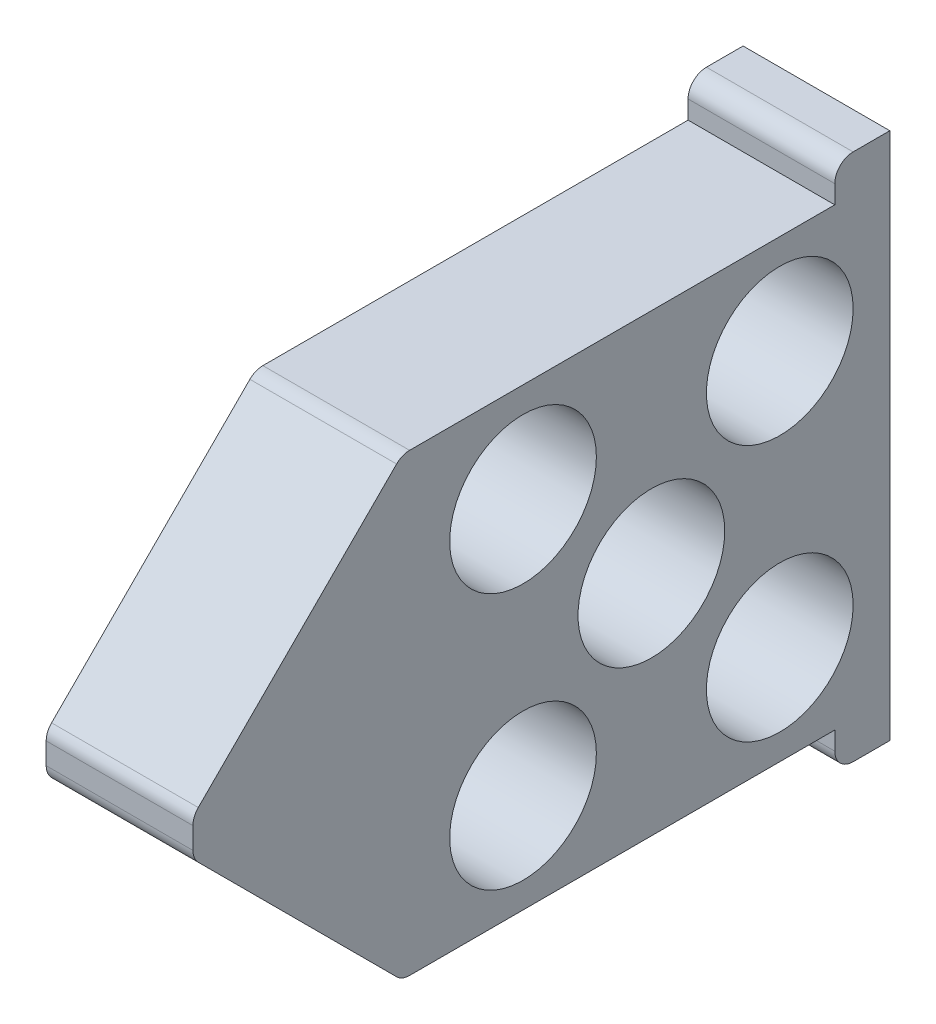
SolidWorks part; units mm, degrees
material "6061-T6 (SS)"
ref_plane "Front Plane" through (0, 0, 0) normal (0, 0, 1) x (1, 0, 0)
ref_plane "Top Plane" through (0, 0, 0) normal (0, 1, 0) x (1, 0, 0)
ref_plane "Right Plane" through (0, 0, 0) normal (1, 0, 0) x (0, 0, -1)
sketch "Sketch1" plane through (0, 0, 0) normal (1, 0, 0) x (0, 0, -1)
  line L0 (-6, 6.2) -> (6, -6.2) construction
  line L2 (-6, 6.2) -> (-6, -6.2) construction
  line L3 (-5.8, 6.2) -> (-11.5, 0.5)
  line L4 (6, 6.2) -> (6, -6.2) construction
  line L5 (6, 6.2) -> (6, 7.2)
  line L6 (6, 7.2) -> (7.5, 7.2)
  line L7 (7.5, 7.2) -> (7.5, -7.2)
  line L8 (-4.2787, 0) -> (7.198, 0) construction
  line L9 (6, -6.2) -> (6, -7.2)
  line L10 (6, -7.2) -> (7.5, -7.2)
  line L11 (6, 6.2) -> (-5.8, 6.2)
  line L12 (-11.5, 6.2) -> (-11.5, -6.2) construction
  line L13 (-11.5, 0.5) -> (-11.5, -0.5)
  line L14 (-5.8, -6.2) -> (-11.5, -0.5)
  line L15 (6, -6.2) -> (-5.8, -6.2)
  point P4 (0, 0)
  point P13 (7.5, 0)
  point P16 (-11.5, 0)
  point P18 (-11.5, 0)
  dimension "D1" = 5.7
  dimension "D2" = 1
  dimension "D3" = 1.5
  dimension "D4" = 1
  dimension "D5" = 17.5
  dimension "D6" = 45
  dimension "D7" = 0.2
extrude "Boss-Extrude1" add sketch "Sketch1" along normal blind 4
fillet "Fillet1" [suppressed] radius 2
fillet "Fillet2" radius 0.5 6 edges at (2, -7.2, -6) (2, 7.2, -6) (2, -6.2, 5.8) (2, -0.5, 11.5) (2, 0.5, 11.5) (2, 6.2, 5.8)
chamfer "Chamfer1" [suppressed] distance 1.9 angle 50
hole_wizard "Ø4.0mm mass reduction holes" positions "Sketch2" profile "Sketch3" hole size "Ø4.0" standard "ANSI Metric"
sketch "Sketch2" plane through (4, 0, 0) normal (1, 0, 0) x (0, 0, -1)
  line L1 (-2.5, 3.5) -> (4.5, 3.5) construction
  line L2 (-2.5, 3.5) -> (-2.5, -3.5) construction
  line L3 (-2.5, -3.5) -> (4.5, -3.5) construction
  line L4 (4.5, 3.5) -> (4.5, -3.5) construction
  line L5 (-2.5, 3.5) -> (4.5, -3.5) construction
  line L6 (-2.5, -3.5) -> (4.5, 3.5) construction
  line L7 (1, 0) -> (0, 0) construction
  point P0 (4.5, -3.5)
  point P2 (4.5, 3.5)
  point P4 (-2.5, -3.5)
  point P6 (-2.5, 3.5)
  point P8 (1, 0)
  point P60 (1, 0)
  dimension "D1" = 7
  dimension "D2" = 7
  dimension "D3" = 1
sketch "Sketch3" plane through (4, -3.5, -4.5) normal (0, 1, 0) x (0, 0, -1)
  line L0 (0, 0) -> (0, 10.7267)
  line L1 (0, 10.7267) -> (2, 9.525)
  line L2 (2, 9.525) -> (2, 0)
  line L5 (2, 0) -> (0, 0)
  line L10 (0, 10.7267) -> (-2, 9.525) construction
  line L11 (0, -6.35) -> (0, 107.95) construction
  dimension "Hole Dia." = 4
  dimension "Hole Depth" = 9.525
  dimension "Drill Angle" = 118
